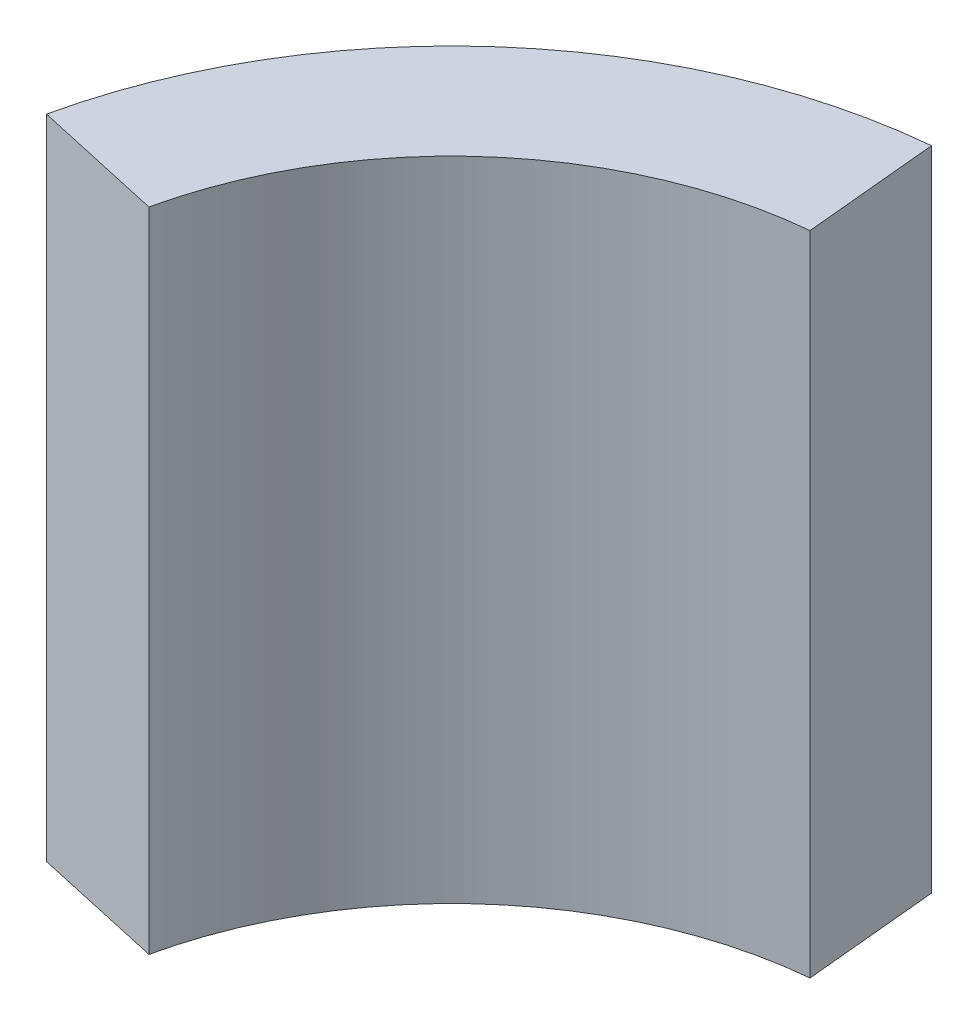
SolidWorks part; units mm, degrees
ref_plane "Front Plane" through (0, 0, 0) normal (0, 0, 1) x (1, 0, 0)
ref_plane "Top Plane" through (0, 0, 0) normal (0, 1, 0) x (1, 0, 0)
ref_plane "Right Plane" through (0, 0, 0) normal (1, 0, 0) x (0, 0, -1)
sketch "Sketch1" plane through (0, 0, 0) normal (0, 1, 0) x (1, 0, -0.0097)
  line L10 (-30.9288, 31.8004) -> (-31.7794, 41.7641)
  line L12 (-66.9171, 11.3164) -> (-57.176, 9.0559)
  arc A1 (-31.7794, 41.7641) -> (-66.9174, 11.3153) centre (-28.4174, 2.3854) ccw
  arc A5 (-30.9288, 31.8004) -> (-57.176, 9.0559) centre (-28.4174, 2.3854) ccw
  dimension "D1" = 29.522
  dimension "D2" = 39.522
extrude "Boss-Extrude1" add sketch "Sketch1" along normal blind 48 contours A5 L10 A1 L12
